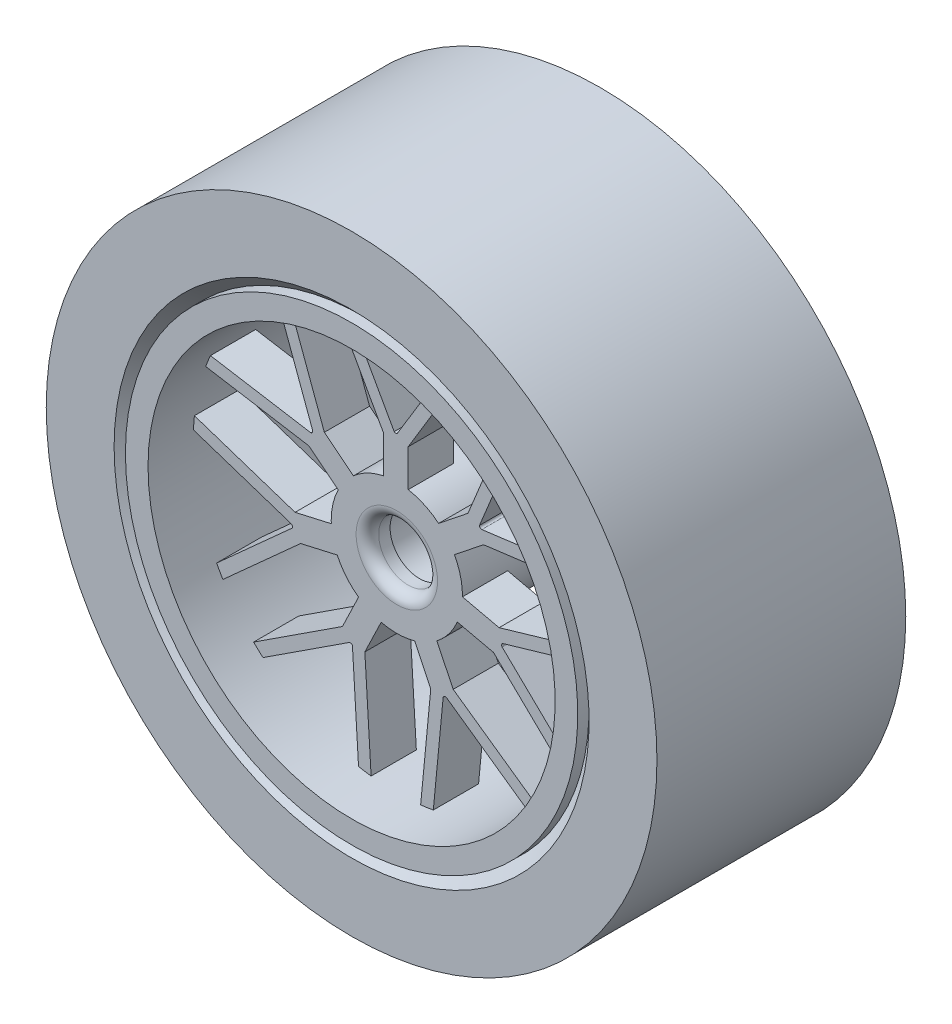
SolidWorks part; units mm, degrees
ref_plane "Front Plane" through (0, 0, 0) normal (0, 0, 1) x (1, 0, 0)
ref_plane "Top Plane" through (0, 0, 0) normal (0, 1, 0) x (1, 0, 0)
ref_plane "Right Plane" through (0, 0, 0) normal (1, 0, 0) x (0, 0, -1)
sketch "Sketch1" plane through (0, 0, 0) normal (0, 1, 0) x (1, 0, 0)
  line L0 (0, 0) -> (0, -12) construction
  line L1 (0, -5.5) -> (-1.4, -5.5) construction
  line L2 (0, -12) -> (-1.3, -12) construction
  line L3 (-1.7, 0) -> (-1.7, -5)
  line L4 (-1.5, -6) -> (-1.4, -5.5)
  line L5 (-1.5, -6) -> (-1.5, -5) construction
  line L7 (0, 0) -> (-1.7, 0) construction
  line L8 (-1.7, -5) -> (-1.4, -5.5)
  line L9 (-1.7, 0) -> (-13.5, 0)
  line L10 (-10, -11) -> (-9, -11)
  line L11 (-10, -11) -> (-10, -10.5)
  line L12 (-13.5, -11) -> (-13.5, 0)
  line L13 (-10, -10.5) -> (-10.5, -11)
  line L14 (-10.5, -11) -> (-13.5, -11)
  line L15 (-1.5, -6) -> (-1.5, -8)
  line L16 (-9, -9) -> (-2.5, -9)
  line L17 (-9, -9) -> (-9, -11)
  line L18 (-2.5, -9) -> (-2.5, -8)
  line L19 (-2.5, -8) -> (-1.5, -8)
  dimension "D1" = 5
  dimension "D2" = 3
  dimension "D3" = 0.5
  dimension "D4" = 0.5
  dimension "D5" = 1.7
  dimension "D6" = 11.8
  dimension "D7" = 1.3
  dimension "D8" = 11
  dimension "D9" = 1.4
  dimension "D11" = 0.5
  dimension "D12" = 1
  dimension "D13" = 2
  dimension "D14" = 1.5
  dimension "D15" = 4
  dimension "D16" = 1
  dimension "D17" = 1
revolve "Revolve1" add sketch "Sketch1" angle 360 about L0
sketch "Sketch2" plane through (0, 0, 9) normal (0, 0, 1) x (1, 0, 0)
  line L0 (0, 2.5) -> (0, 4.5) construction
  line L1 (-0.5978, 4.5) -> (-2.8489, 8.5372)
  line L2 (-0.5978, 4.5) -> (-1.1619, 5.477) construction
  line L3 (0, 4.5) -> (-0.5978, 4.5) construction
  line L4 (0, 4.5) -> (0.5022, 4.5) construction
  line L5 (-0.5978, 4.5) -> (-0.5978, 2.4275)
  line L6 (0.5022, 4.5) -> (0.5022, 2.449)
  line L7 (-0.5978, 4.5) -> (-0.1175, 4.7678) construction
  line L8 (0.5022, 4.5) -> (0.0317, 4.7848) construction
  line L9 (0.5022, 4.5) -> (1.073, 5.4887) construction
  line L10 (0.5022, 4.5) -> (2.9297, 8.5098)
  line L11 (-1.4053, 5.9481) -> (-0.9249, 6.216) construction
  line L12 (-2.3421, 7.6284) -> (-1.8618, 7.8962) construction
  line L13 (1.4938, 6.1379) -> (1.0233, 6.4228) construction
  line L14 (2.2274, 7.3498) -> (1.7569, 7.6346) construction
  line L15 (-0.1175, 4.7678) -> (-2.3421, 8.7578)
  line L16 (-2.3421, 8.7578) -> (-2.8489, 8.5372)
  line L17 (0.0317, 4.7848) -> (2.4369, 8.7578)
  line L18 (2.4369, 8.7578) -> (2.9297, 8.5098)
  arc A0 (-0.1175, 4.7678) -> (0.0317, 4.7848) centre (-0.0514, 4.8509) ccw
  circle A4 centre (0, 0) radius 2.5 construction
  circle A5 centre (0, 0) radius 2.5 construction
  circle A7 centre (0, 0) radius 9 construction
  arc A8 (-0.5978, 2.4275) -> (0.5022, 2.449) centre (-0.004, 0.2054) cw
  dimension "D1" = 1.1
  dimension "D2" = 2
  dimension "D3" = 150
  dimension "D5" = 150
sketch "Sketch3" plane through (0, 0, 0) normal (0, 0, -1) x (-1, 0, 0)
  circle A0 centre (0, 0) radius 9
  circle A1 centre (0, 0) radius 2.9
extrude "Cut-Extrude1" cut sketch "Sketch3" against normal blind 9
extrude "Boss-Extrude1" add sketch "Sketch2" against normal blind 2
pattern_circular "CirPattern1" count 7 over 360 about axis through (0, 0, 0) along (0, 0, 1) of "Boss-Extrude1"
sketch "Sketch5" plane through (0, 0, 8) normal (0, 0, 1) x (1, 0, 0)
  circle A0 centre (0, 0) radius 2.9
  circle A1 centre (0, 0) radius 1.3
extrude "Boss-Extrude2" add sketch "Sketch5" along normal blind 1
fillet "Fillet2" radius 0.5 1 edges at (1.3, 0, 9)
